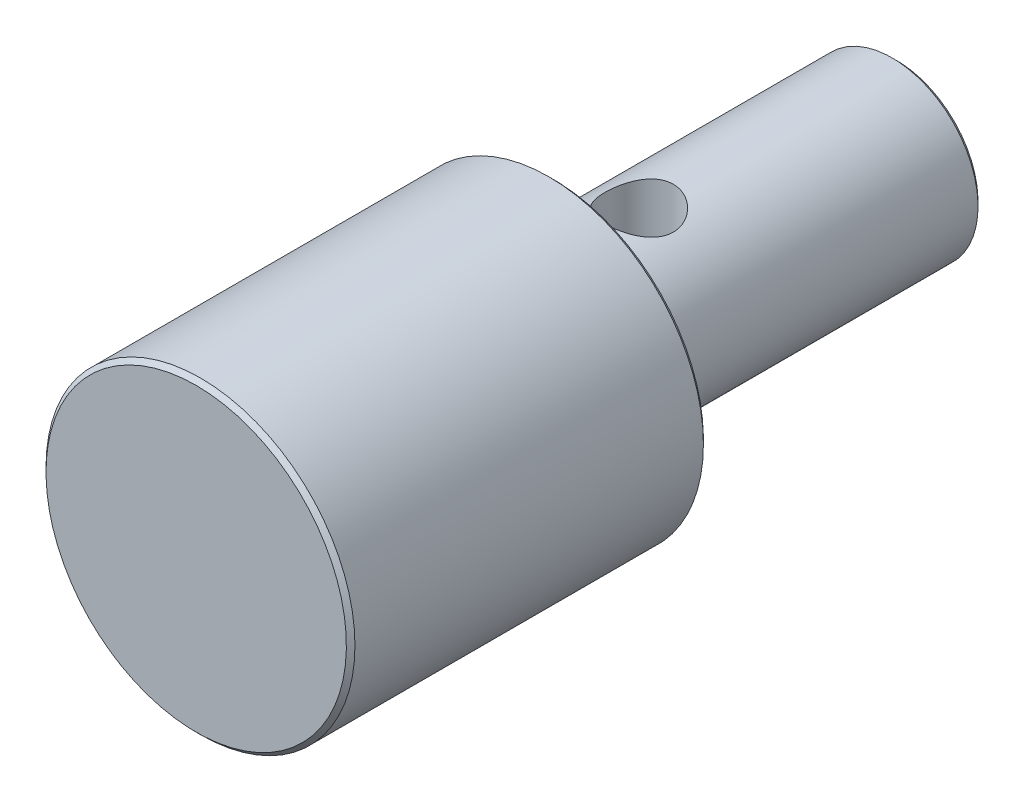
SolidWorks part; units mm, degrees
ref_plane "Спереди" through (0, 0, 0) normal (0, 0, 1) x (1, 0, 0)
ref_plane "Сверху" through (0, 0, 0) normal (0, 1, 0) x (1, 0, 0)
ref_plane "Справа" through (0, 0, 0) normal (1, 0, 0) x (0, 0, -1)
sketch "Эскиз1" plane through (0, 0, 0) normal (1, 0, 0) x (0, 0, -1)
  line L0 (0, 0) -> (0, 18)
  line L1 (0, 18) -> (41.6, 18)
  line L2 (41.6, 18) -> (41.6, 10)
  line L3 (41.6, 10) -> (81.6, 10)
  line L4 (81.6, 10) -> (81.6, 0)
  line L5 (0, 0) -> (81.6, 0)
  dimension "D1" = 41.6
  dimension "D2" = 18
  dimension "D3" = 8
  dimension "D4" = 40
  dimension "D5" = 10
revolve "Повернуть1" add sketch "Эскиз1" angle 360 about L5
ref_plane "Плоскость1" through (0, 10, 0) normal (0, 1, 0) x (1, 0, 0)
sketch "Эскиз2" plane through (0, 10, 0) normal (0, 1, 0) x (1, 0, 0)
  line L0 (10, 41.6) -> (10, 81.6) construction
  line L1 (18, 41.6) -> (-18, 41.6) construction
  circle A0 centre (0, 51.6) radius 4
  dimension "D1" = 8
  dimension "D2" = 10
  dimension "D3" = 10
extrude "Вырез-Вытянуть1" cut sketch "Эскиз2" against normal through all
fillet "Скругление1" radius 0.5 1 edges at (0, -10, -41.6)
chamfer "Фаска1" distance 0.5 angle 45 3 edges at (0, -18, 0) (0, -18, -41.6) (0, -10, -81.6)
